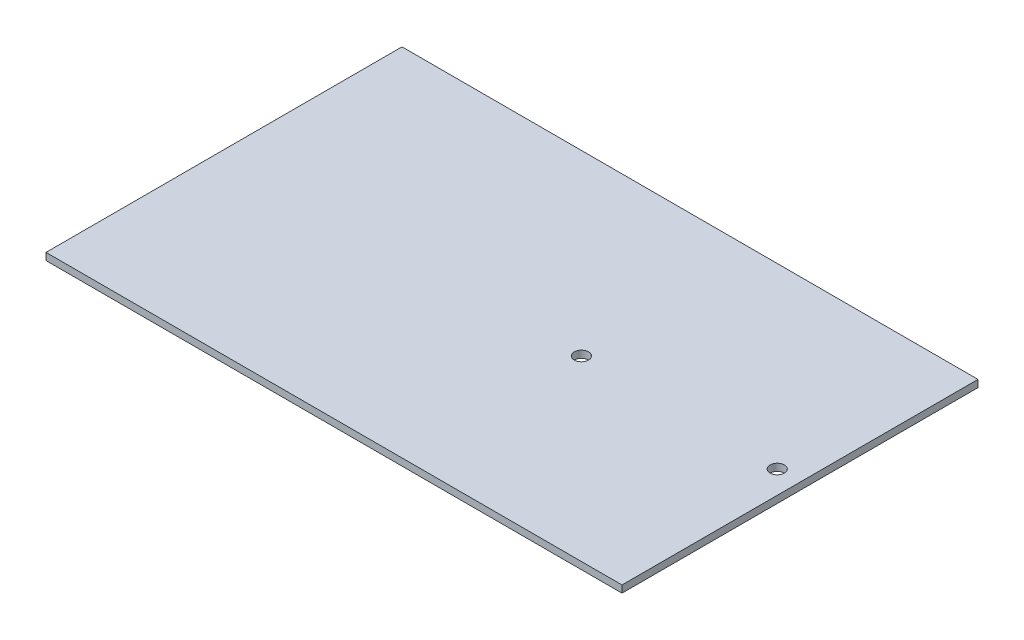
SolidWorks part; units mm, degrees
ref_plane "Plano frontal" through (0, 0, 0) normal (0, 0, 1) x (1, 0, 0)
ref_plane "Plano superior" through (0, 0, 0) normal (0, 1, 0) x (1, 0, 0)
ref_plane "Plano direito" through (0, 0, 0) normal (1, 0, 0) x (0, 0, -1)
sketch "Esboço1" plane through (0, 0, 0) normal (0, 1, 0) x (1, 0, 0)
  line L1 (-40.45, -25) -> (40.45, -25)
  line L2 (-40.45, -25) -> (-40.45, 25)
  line L3 (-40.45, 25) -> (40.45, 25)
  line L4 (40.45, -25) -> (40.45, 25)
  line L5 (-40.45, -25) -> (40.45, 25) construction
  line L6 (-40.45, 25) -> (40.45, -25) construction
  point P0 (0, 0)
  dimension "D1" = 50
  dimension "D2" = 80.9
extrude "Ressalto-extrusão1" add sketch "Esboço1" along normal blind 1
sketch "Esboço2" plane through (0, 1, 0) normal (0, 1, 0) x (1, 0, 0)
  line L0 (40.45, -25) -> (40.45, 25) construction
  circle A0 centre (37.25, 0) radius 1
  circle A1 centre (9.75, 0) radius 1
  dimension "D1" = 3.2
  dimension "D2" = 27.5
extrude "Corte-extrusão1" cut sketch "Esboço2" against normal through all
